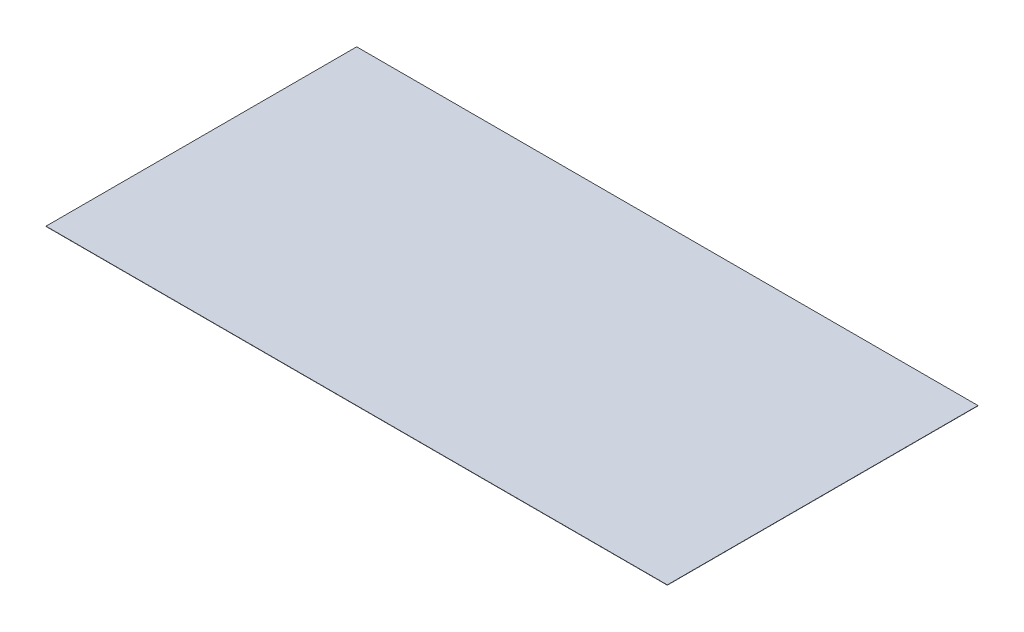
SolidWorks part; units mm, degrees
ref_plane "Front Plane" through (0, 0, 0) normal (0, 0, 1) x (1, 0, 0)
ref_plane "Top Plane" through (0, 0, 0) normal (0, 1, 0) x (1, 0, 0)
ref_plane "Right Plane" through (0, 0, 0) normal (1, 0, 0) x (0, 0, -1)
sketch "Sketch1" plane through (0, 0, 0) normal (0, 1, 0) x (1, 0, 0)
  line L1 (0, 0) -> (2438.4, 0)
  line L2 (0, 0) -> (0, 1219.2)
  line L3 (0, 1219.2) -> (2438.4, 1219.2)
  line L4 (2438.4, 0) -> (2438.4, 1219.2)
  dimension "D1" = 1219.2
  dimension "D2" = 2438.4
extrude "Boss-Extrude1" add sketch "Sketch1" along normal blind 1
